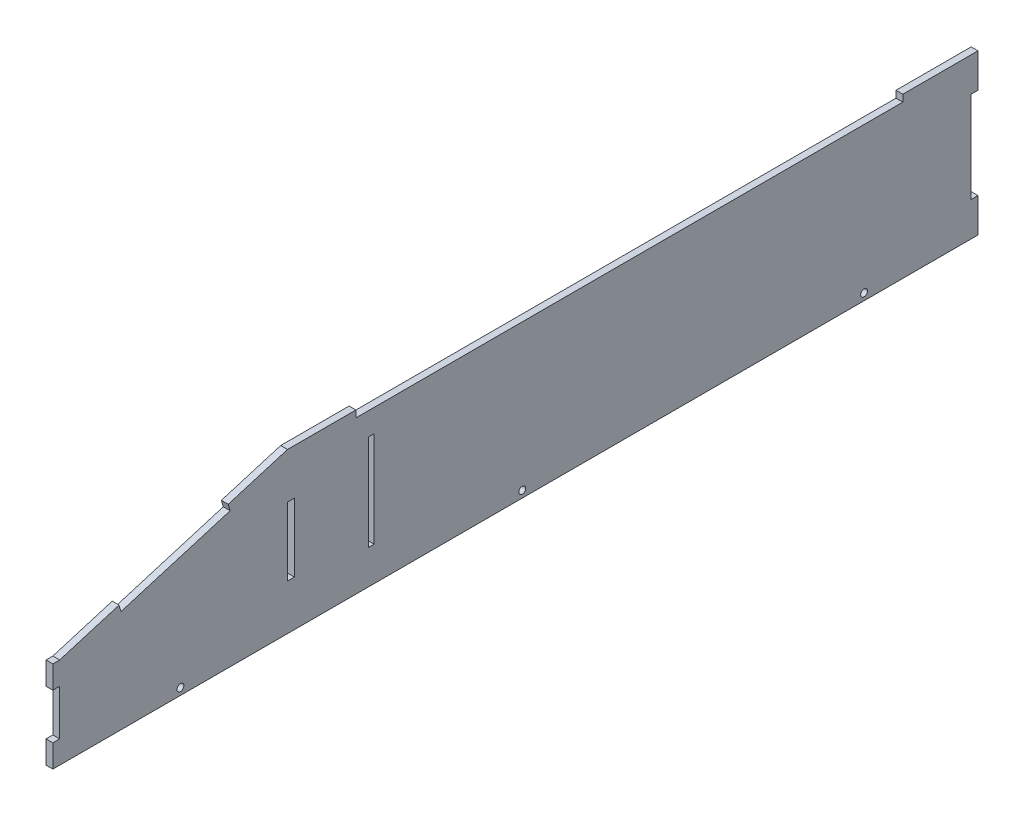
SolidWorks part; units mm, degrees
ref_plane "Front Plane" through (0, 0, 0) normal (0, 0, 1) x (1, 0, 0)
ref_plane "Top Plane" through (0, 0, 0) normal (0, 1, 0) x (1, 0, 0)
ref_plane "Right Plane" through (0, 0, 0) normal (1, 0, 0) x (0, 0, -1)
sketch "Sketch1" plane through (0, 0, 0) normal (1, 0, 0) x (0, 0, -1)
  line L0 (286.1443, 0.1739) -> (286.1443, 70.1739)
  line L1 (-16.8557, 70.1739) -> (286.1443, 70.1739)
  line L6 (-119.8557, 40.1739) -> (-116.8557, 40.1739)
  line L7 (-116.8557, 40.1739) -> (-16.8557, 70.1739)
  line L11 (-119.8557, 40.1739) -> (-119.8557, 0.1739)
  line L12 (-119.8557, 0.1739) -> (286.1443, 0.1739)
  dimension "D1" = 406
  dimension "D2" = 303
  dimension "D4" = 3
  dimension "D6" = 70
  dimension "D7" = 40
extrude "Boss-Extrude1" add sketch "Sketch1" along normal blind 3
sketch "Sketch5" plane through (3, 0, 0) normal (1, 0, 0) x (0, 0, -1)
  line L0 (286.1443, 55.1739) -> (283.1443, 55.1739)
  line L1 (286.1443, 0.1739) -> (286.1443, 70.1739) construction
  line L2 (283.1443, 55.1739) -> (283.1443, 15.1739)
  line L3 (283.1443, 15.1739) -> (286.1443, 15.1739)
  line L4 (-119.8557, 0.1739) -> (286.1443, 0.1739) construction
  dimension "D1" = 3
  dimension "D2" = 40
  dimension "D3" = 15
extrude "Cut-Extrude2" cut sketch "Sketch5" against normal blind 3 and the other way through all
sketch "Sketch6" plane through (3, 0, 0) normal (1, 0, 0) x (0, 0, -1)
  line L0 (253.1443, 70.1739) -> (253.1443, 67.1739)
  line L1 (286.1443, 70.1739) -> (-16.8557, 70.1739) construction
  line L2 (253.1443, 67.1739) -> (13.1443, 67.1739)
  line L3 (13.1443, 67.1739) -> (13.1443, 70.1739)
  line L4 (286.1443, 55.1739) -> (286.1443, 70.1739) construction
  dimension "D1" = 3
  dimension "D2" = 240
  dimension "D3" = 33
extrude "Cut-Extrude6" cut sketch "Sketch6" against normal blind 3 and the other way through all flip side to cut
sketch "Sketch7" plane through (3, 0, 0) normal (1, 0, 0) x (0, 0, -1)
  line L0 (-42.9086, 62.358) -> (-42.0465, 59.4846)
  line L1 (-16.8557, 70.1739) -> (-116.8557, 40.1739) construction
  line L2 (-42.0465, 59.4846) -> (-89.9378, 45.1172)
  line L3 (-89.9378, 45.1172) -> (-90.7999, 47.9906)
  dimension "D1" = 3
  dimension "D2" = 50
  dimension "D3" = 27.2
  dimension "D4" = 27.2031
extrude "Cut-Extrude11" cut sketch "Sketch7" against normal blind 3 and the other way through all flip side to cut
sketch "Sketch8" plane through (3, 0, 0) normal (1, 0, 0) x (0, 0, -1)
  line L0 (-119.8557, 30.1739) -> (-116.8557, 30.1739)
  line L1 (-119.8557, 40.1739) -> (-119.8557, 0.1739) construction
  line L2 (-116.8557, 30.1739) -> (-116.8557, 10.1739)
  line L3 (-116.8557, 10.1739) -> (-119.8557, 10.1739)
  line L4 (-119.8557, 0.1739) -> (286.1443, 0.1739) construction
  dimension "D1" = 3
  dimension "D2" = 20
  dimension "D3" = 10
extrude "Cut-Extrude12" cut sketch "Sketch8" against normal blind 3 and the other way through all flip side to cut
sketch "Sketch9" plane through (3, 0, 0) normal (1, 0, 0) x (0, 0, -1)
  line L0 (-16.8557, 50.1739) -> (-16.8557, 20.1739)
  line L1 (-16.8557, 20.1739) -> (-13.8557, 20.1739)
  line L2 (-13.8557, 20.1739) -> (-13.8557, 50.1739)
  line L3 (-13.8557, 50.1739) -> (-16.8557, 50.1739)
  line L4 (-119.8557, 0.1739) -> (286.1443, 0.1739) construction
  dimension "D1" = 30
  dimension "D2" = 20
  dimension "D3" = 3
extrude "Cut-Extrude13" cut sketch "Sketch9" against normal blind 3
sketch "Sketch10" plane through (3, 0, 0) normal (1, 0, 0) x (0, 0, -1)
  line L0 (-13.8557, 20.1739) -> (-13.8557, 50.1739) construction
  line L1 (21.1443, 57.1739) -> (18.6443, 57.1739)
  line L2 (21.1443, 57.1739) -> (21.1443, 15.1739)
  line L3 (21.1443, 15.1739) -> (18.6443, 15.1739)
  line L4 (18.6443, 57.1739) -> (18.6443, 15.1739)
  line L5 (-119.8557, 0.1739) -> (286.1443, 0.1739) construction
  line L6 (253.1443, 67.1739) -> (13.1443, 67.1739) construction
  dimension "D1" = 35
  dimension "D2" = 15
  dimension "D3" = 10
  dimension "D4" = 2.5
extrude "Cut-Extrude14" cut sketch "Sketch10" against normal blind 10
sketch "Sketch11" plane through (3, 0, 0) normal (1, 0, 0) x (0, 0, -1)
  line L0 (-119.8557, 0.1739) -> (286.1443, 0.1739) construction
  line L1 (286.1443, 0.1739) -> (286.1443, 15.1739) construction
  circle A0 centre (236.1443, 3.1739) radius 1.5
  circle A1 centre (86.1443, 3.1739) radius 1.5
  circle A2 centre (-63.8557, 3.1739) radius 1.5
  dimension "D1" = 3
  dimension "D2" = 3
  dimension "D3" = 50
  dimension "D4" = 3
extrude "Cut-Extrude15" cut sketch "Sketch11" against normal blind 10
